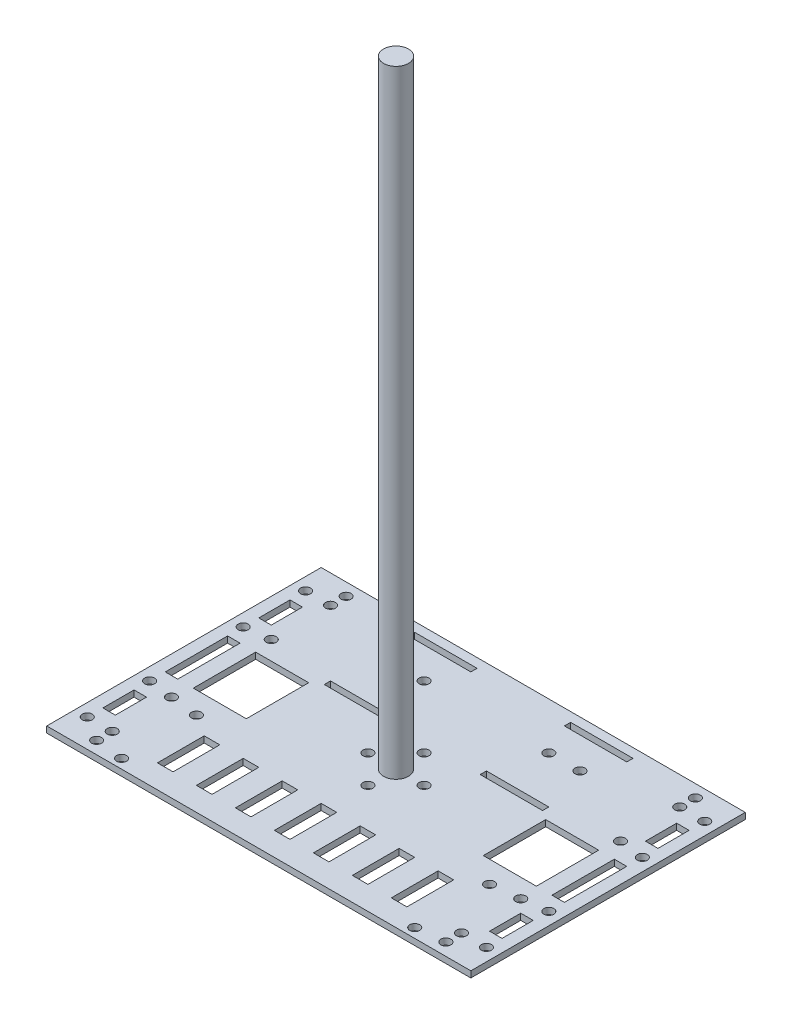
SolidWorks part; units mm, degrees
ref_plane "前视基准面" through (0, 0, 0) normal (0, 0, 1) x (1, 0, 0)
ref_plane "上视基准面" through (0, 0, 0) normal (0, 1, 0) x (1, 0, 0)
ref_plane "右视基准面" through (0, 0, 0) normal (1, 0, 0) x (0, 0, -1)
sketch "草图1" plane through (0, 0, 0) normal (0, 1, 0) x (1, 0, 0)
  line L1 (0, 0) -> (136, 0)
  line L2 (0, 0) -> (0, -88)
  line L3 (0, -88) -> (136, -88)
  line L4 (136, 0) -> (136, -88)
  dimension "D1" = 136
  dimension "D2" = 88
extrude "凸台-拉伸1" add sketch "草图1" along normal blind 2
sketch "草图2" plane through (0, 2, 0) normal (0, 1, 0) x (1, 0, 0)
  line L0 (0, 0) -> (136, -88) construction
  line L1 (0, -88) -> (136, 0) construction
  line L2 (58, -44) -> (83.8346, -44) construction
  line L3 (68, -44) -> (68, -21.8619) construction
  line L4 (0, -44) -> (4, -44) construction
  line L5 (0, 0) -> (0, -88) construction
  line L6 (4, -44) -> (8, -44) construction
  line L7 (4, -44) -> (4, -29) construction
  line L8 (4, -29) -> (4, -9) construction
  line L9 (4, -44) -> (4, -34)
  line L10 (4, -34) -> (8, -34)
  line L11 (8, -34) -> (8, -44)
  line L12 (132, -29) -> (132, -9) construction
  line L13 (4, -24) -> (8, -24)
  line L14 (4, -24) -> (4, -14)
  line L15 (4, -14) -> (8, -14)
  line L16 (8, -24) -> (8, -14)
  line L17 (132, -59) -> (132, -29) construction
  line L18 (132, -44) -> (128, -44) construction
  line L19 (136, -44) -> (132, -44) construction
  line L20 (128, -24) -> (128, -14)
  line L21 (132, -14) -> (128, -14)
  line L22 (132, -24) -> (132, -14)
  line L23 (132, -24) -> (128, -24)
  line L24 (128, -34) -> (128, -54)
  line L25 (132, -34) -> (128, -34)
  line L26 (132, -54) -> (132, -34)
  line L27 (132, -59) -> (132, -79) construction
  line L28 (0, 0) -> (136, -88) construction
  line L29 (132, -54) -> (128, -54)
  line L30 (132, -64) -> (128, -64)
  line L31 (132, -64) -> (132, -74)
  line L32 (132, -74) -> (128, -74)
  line L33 (128, -64) -> (128, -74)
  line L34 (4, -59) -> (4, -79) construction
  line L35 (8, -64) -> (8, -74)
  line L36 (4, -74) -> (8, -74)
  line L37 (4, -64) -> (4, -74)
  line L38 (4, -64) -> (8, -64)
  line L39 (4, -54) -> (8, -54)
  line L40 (4, -54) -> (4, -44)
  line L41 (8, -54) -> (8, -44)
  circle A0 centre (4, -29) radius 1.6
  circle A1 centre (4, -9) radius 1.6
  circle A2 centre (132, -9) radius 1.6
  circle A3 centre (132, -29) radius 1.6
  circle A4 centre (132, -59) radius 1.6
  circle A5 centre (132, -79) radius 1.6
  circle A6 centre (4, -79) radius 1.6
  circle A7 centre (4, -59) radius 1.6
  point P10 (68, -44)
  dimension "D5" = 3.2
  dimension "D6" = 3.2
  dimension "D7" = 10
  dimension "D1" = 4
  dimension "D2" = 4
  dimension "D3" = 20
  dimension "D4" = 15
  dimension "D8" = 10
  dimension "D9" = 20
  dimension "D10" = 4
extrude "切除-拉伸1" cut sketch "草图2" against normal blind 2
sketch "草图4" plane through (0, 2, 0) normal (0, 1, 0) x (1, 0, 0)
  line L0 (68, 0) -> (68, -88) construction
  line L1 (136, 0) -> (0, 0) construction
  line L2 (0, -88) -> (136, -88) construction
sketch "草图5" plane through (0, 2, 0) normal (0, 1, 0) x (1, 0, 0)
  line L0 (0, -44) -> (136, -44) construction
  line L1 (0, 0) -> (0, -88) construction
  line L2 (136, -88) -> (136, 0) construction
  line L3 (12, -44) -> (12, -28) construction
  line L4 (12, -44) -> (12, -60) construction
  line L5 (68, 0) -> (68, -88) construction
  line L6 (0, -88) -> (136, -88) construction
  line L7 (12, -60) -> (12, -88) construction
  line L8 (12, -28) -> (12, 0) construction
  line L9 (136, 0) -> (0, 0) construction
  circle A0 centre (12, -28) radius 1.6
  circle A1 centre (12, -60) radius 1.6
  circle A2 centre (124, -60) radius 1.6
  circle A3 centre (124, -28) radius 1.6
  circle A8 centre (12, -79) radius 1.6
  circle A9 centre (12, -84) radius 1.6
  circle A10 centre (12, -9) radius 1.6
  circle A11 centre (12, -4) radius 1.6
  circle A12 centre (124, -84) radius 1.6
  circle A13 centre (124, -79) radius 1.6
  circle A14 centre (124, -4) radius 1.6
  circle A15 centre (124, -9) radius 1.6
  dimension "D4" = 3.2
  dimension "D5" = 3.2
  dimension "D6" = 4
  dimension "D7" = 5
  dimension "D8" = 4
  dimension "D9" = 5
  dimension "D10" = 3.2
  dimension "D11" = 3.2
  dimension "D12" = 3.2
  dimension "D13" = 3.2
  dimension "D1" = 16
  dimension "D2" = 16
  dimension "D3" = 12
extrude "切除-拉伸2" cut sketch "草图5" against normal blind 10
sketch "草图6" plane through (0, 2, 0) normal (0, 1, 0) x (1, 0, 0)
  line L0 (68, 0) -> (68, -88) construction
  circle A0 centre (68, -44) radius 9 construction
  circle A1 centre (68, -35) radius 1.6
  circle A2 centre (68, -53) radius 1.6
  circle A3 centre (77, -44) radius 1.6
  circle A4 centre (59, -44) radius 1.6
  dimension "D1" = 18
  dimension "D2" = 3.2
  dimension "D3" = 3.2
  dimension "D4" = 3.2
  dimension "D5" = 3.2
extrude "切除-拉伸3" cut sketch "草图6" against normal blind 10
sketch "草图7" plane through (0, 2, 0) normal (0, 1, 0) x (1, 0, 0)
  line L0 (68, 0) -> (68, -88) construction
  circle A0 centre (68, -44) radius 12
  dimension "D1" = 24
sketch "草图10" plane through (0, 2, 0) normal (0, 1, 0) x (1, 0, 0)
  line L0 (18, -73) -> (118, -73) construction
  line L5 (68, -88) -> (68, -58) construction
  line L8 (0, -88) -> (136, -88) construction
  line L9 (18, -58) -> (118, -58) construction
  line L10 (18, -58) -> (18, -88) construction
  line L11 (18, -88) -> (118, -88) construction
  line L12 (118, -58) -> (118, -88) construction
  line L17 (18, -58) -> (118, -88) construction
  line L18 (18, -88) -> (118, -58) construction
  circle A4 centre (21, -85) radius 1.6
  circle A5 centre (21, -61) radius 1.6
  circle A6 centre (115, -61) radius 1.6
  circle A7 centre (115, -85) radius 1.6
  point P2 (68, -73)
  dimension "D5" = 3
  dimension "D6" = 3.2
  dimension "D7" = 3
  dimension "D1" = 30
  dimension "D2" = 100
  dimension "D3" = 30
  dimension "D4" = 3
extrude "切除-拉伸4" cut sketch "草图10" against normal blind 10
sketch "草图11" plane through (0, 0, 0) normal (0, -1, 0) x (1, 0, 0)
  circle A0 centre (68, 44) radius 4
  dimension "D1" = 8
extrude "凸台-拉伸3" add sketch "草图11" against normal blind 200
sketch "草图12" plane through (0, 2, 0) normal (0, 1, 0) x (1, 0, 0)
  line L0 (68, 0) -> (28, 0)
  line L1 (136, 0) -> (0, 0) construction
  line L2 (28, 0) -> (28, 12)
  line L3 (28, 12) -> (108, 12)
  line L4 (108, 12) -> (108, 0)
  line L5 (108, 0) -> (68, 0)
  dimension "D1" = 40
  dimension "D2" = 40
  dimension "D3" = 12
sketch "草图13" plane through (0, 2, 0) normal (0, 1, 0) x (1, 0, 0)
  line L0 (68, 0) -> (28, 0) construction
  line L1 (68, 0) -> (68, -88) construction
  line L2 (68, -3) -> (53, -3) construction
  line L3 (68, -3) -> (83, -3) construction
  line L4 (53, -3) -> (33, -3)
  line L5 (33, -3) -> (33, -5)
  line L6 (33, -5) -> (53, -5)
  line L7 (53, -5) -> (53, -3)
  line L8 (83, -3) -> (103, -3)
  line L9 (103, -3) -> (103, -5)
  line L10 (103, -5) -> (83, -5)
  line L11 (83, -5) -> (83, -3)
  line L12 (33, -5) -> (33, -30)
  line L14 (33, -30) -> (53, -30)
  line L15 (33, -30) -> (33, -32)
  line L16 (33, -32) -> (53, -32)
  line L17 (53, -30) -> (53, -32)
  line L18 (83, -30) -> (103, -30)
  line L19 (83, -30) -> (83, -32)
  line L20 (83, -32) -> (103, -32)
  line L21 (103, -30) -> (103, -32)
  dimension "D1" = 15
  dimension "D2" = 15
  dimension "D3" = 2
  dimension "D4" = 2
  dimension "D5" = 20
  dimension "D6" = 20
  dimension "D7" = 3
  dimension "D8" = 25
  dimension "D9" = 20
  dimension "D10" = 2
  dimension "D11" = 2
  dimension "D12" = 20
  dimension "D13" = 70
  dimension "D14" = 29
extrude "切除-拉伸5" cut sketch "草图13" against normal blind 2 contours L6 L7 L4 L5 | L17 L14 L15 L16 | L21 L18 L19 L20 | L8 L9 L10 L11
sketch "草图14" plane through (0, 2, 0) normal (0, 1, 0) x (1, 0, 0)
  line L0 (0, -44) -> (13, -44) construction
  line L1 (0, 0) -> (0, -88) construction
  line L2 (13, -44) -> (13, -34)
  line L3 (13, -34) -> (30, -34)
  line L4 (30, -34) -> (30, -54)
  line L5 (30, -54) -> (13, -54)
  line L6 (13, -54) -> (13, -44)
  line L7 (68, 0) -> (68, -88) construction
  line L8 (106, -34) -> (106, -54)
  line L9 (106, -54) -> (123, -54)
  line L10 (123, -54) -> (123, -44)
  line L11 (123, -44) -> (123, -34)
  line L12 (123, -34) -> (106, -34)
  dimension "D1" = 13
  dimension "D2" = 30
  dimension "D3" = 20
  dimension "D4" = 10
extrude "切除-拉伸6" cut sketch "草图14" against normal blind 10
sketch "草图15" plane through (0, 2, 0) normal (0, 1, 0) x (1, 0, 0)
  line L0 (68, 0) -> (68, -88) construction
  line L1 (0, -88) -> (136, -88) construction
  line L2 (65.5, -65.5) -> (70.5, -65.5)
  line L3 (65.5, -65.5) -> (65.5, -80.5)
  line L4 (65.5, -80.5) -> (70.5, -80.5)
  line L5 (70.5, -65.5) -> (70.5, -80.5)
  line L6 (65.5, -65.5) -> (70.5, -80.5) construction
  line L7 (65.5, -80.5) -> (70.5, -65.5) construction
  line L8 (78, -65.5) -> (83, -65.5)
  line L9 (78, -65.5) -> (78, -80.5)
  line L10 (78, -80.5) -> (83, -80.5)
  line L11 (83, -65.5) -> (83, -80.5)
  line L12 (78, -65.5) -> (83, -80.5) construction
  line L13 (78, -80.5) -> (83, -65.5) construction
  line L14 (90.5, -65.5) -> (95.5, -65.5)
  line L15 (90.5, -65.5) -> (90.5, -80.5)
  line L16 (90.5, -80.5) -> (95.5, -80.5)
  line L17 (95.5, -65.5) -> (95.5, -80.5)
  line L18 (90.5, -65.5) -> (95.5, -80.5) construction
  line L19 (90.5, -80.5) -> (95.5, -65.5) construction
  line L20 (103, -65.5) -> (108, -65.5)
  line L21 (103, -65.5) -> (103, -80.5)
  line L22 (103, -80.5) -> (108, -80.5)
  line L23 (108, -65.5) -> (108, -80.5)
  line L24 (103, -65.5) -> (108, -80.5) construction
  line L25 (103, -80.5) -> (108, -65.5) construction
  line L27 (53, -65.5) -> (58, -65.5)
  line L28 (53, -65.5) -> (53, -80.5)
  line L29 (53, -80.5) -> (58, -80.5)
  line L30 (58, -65.5) -> (58, -80.5)
  line L31 (53, -65.5) -> (58, -80.5) construction
  line L32 (53, -80.5) -> (58, -65.5) construction
  line L33 (40.5, -65.5) -> (45.5, -65.5)
  line L34 (40.5, -65.5) -> (40.5, -80.5)
  line L35 (40.5, -80.5) -> (45.5, -80.5)
  line L36 (45.5, -65.5) -> (45.5, -80.5)
  line L37 (40.5, -65.5) -> (45.5, -80.5) construction
  line L38 (40.5, -80.5) -> (45.5, -65.5) construction
  line L39 (28, -65.5) -> (33, -65.5)
  line L40 (28, -65.5) -> (28, -80.5)
  line L41 (28, -80.5) -> (33, -80.5)
  line L42 (33, -65.5) -> (33, -80.5)
  line L43 (28, -65.5) -> (33, -80.5) construction
  line L44 (28, -80.5) -> (33, -65.5) construction
  point P2 (68, -73)
  point P7 (80.5, -73)
  point P12 (93, -73)
  point P17 (105.5, -73)
  point P24 (55.5, -73)
  point P29 (43, -73)
  point P34 (30.5, -73)
  dimension "D1" = 15
  dimension "D2" = 5
  dimension "D3" = 15
  dimension "D4" = 7.5
  dimension "D5" = 7.5
  dimension "D6" = 7.5
  dimension "D7" = 5
  dimension "D8" = 5
  dimension "D9" = 5
  dimension "D10" = 15
  dimension "D11" = 15
  dimension "D12" = 15
  dimension "D13" = 5
  dimension "D14" = 5
  dimension "D15" = 5
  dimension "D16" = 7.5
  dimension "D17" = 7.5
  dimension "D18" = 15
  dimension "D19" = 15
  dimension "D20" = 15
  dimension "D21" = 7.5
extrude "切除-拉伸7" cut sketch "草图15" against normal blind 5
sketch "草图16" plane through (0, 0, 0) normal (0, -1, 0) x (1, 0, 0)
  line L0 (88, 15) -> (48, 15) construction
  line L1 (108, 0) -> (68, 0) construction
  line L3 (68, 0) -> (68, 88) construction
  line L4 (88, 15) -> (98, 15) construction
  line L5 (48, 15) -> (38, 15) construction
  circle A0 centre (88, 15) radius 1.6
  circle A1 centre (48, 15) radius 1.6
  circle A2 centre (98, 15) radius 1.6
  circle A3 centre (38, 15) radius 1.6
  point P5 (68, 15)
  dimension "D5" = 3.2
  dimension "D6" = 3.2
  dimension "D7" = 3.2
  dimension "D8" = 3.2
  dimension "D1" = 15
  dimension "D2" = 40
  dimension "D3" = 10
  dimension "D4" = 10
extrude "切除-拉伸8" cut sketch "草图16" against normal blind 10
